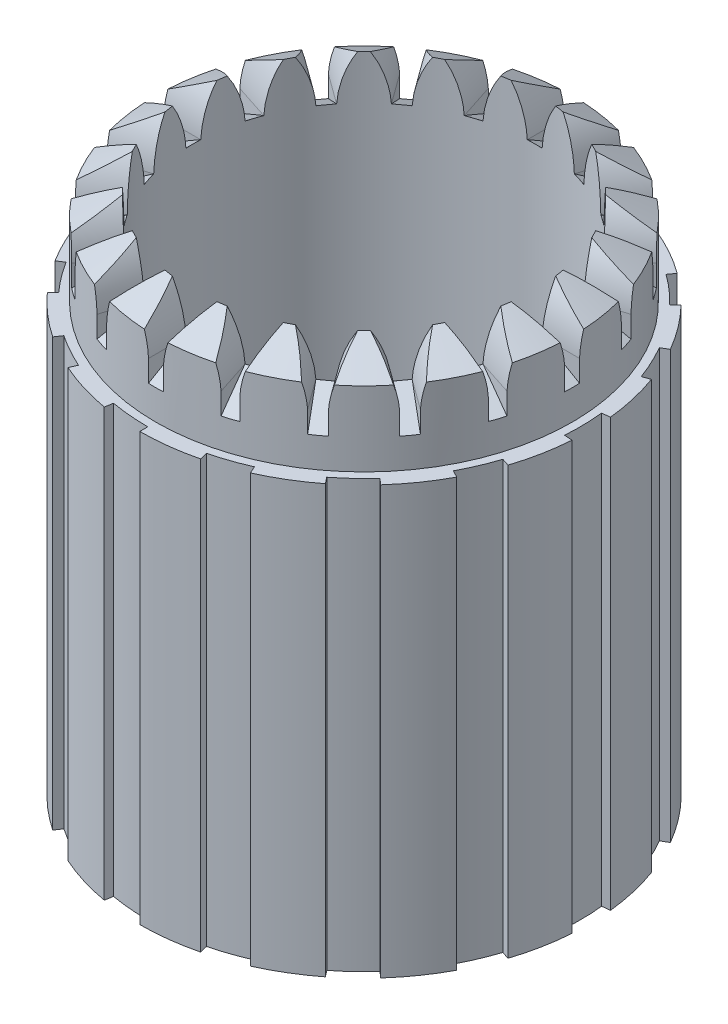
SolidWorks part; units mm, degrees
ref_plane "Front Plane" through (0, 0, 0) normal (0, 0, 1) x (1, 0, 0)
ref_plane "Top Plane" through (0, 0, 0) normal (0, 1, 0) x (1, 0, 0)
ref_plane "Right Plane" through (0, 0, 0) normal (1, 0, 0) x (0, 0, -1)
sketch "Sketch1" plane through (0, 0, 0) normal (0, 1, 0) x (1, 0, 0)
  circle A0 centre (0, 0) radius 21
  dimension "D1" = 42
extrude "Boss-Extrude1" add sketch "Sketch1" along normal blind 40
sketch "Sketch3" plane through (0, 40, 0) normal (0, 1, 0) x (1, 0, 0)
  circle A0 centre (0, 0) radius 19.5
  dimension "D1" = 39
extrude "Boss-Extrude2" add sketch "Sketch3" along normal blind 9
sketch "Sketch4" plane through (0, 49, 0) normal (0, 1, 0) x (1, 0, 0)
  circle A0 centre (0, 0) radius 16
  dimension "D1" = 32
extrude "Cut-Extrude1" cut sketch "Sketch4" against normal blind 59
sketch "Sketch5" plane through (0, 0, 0) normal (0, -1, 0) x (1, 0, 0)
  line L0 (0, 21) -> (0, -21) construction
  line L1 (0, 21) -> (0, 20.25)
  line L2 (5.0804, 20.3762) -> (4.8989, 19.6485)
  line L3 (12.9289, 16.5482) -> (12.4671, 15.9572)
  line L4 (8.5415, 19.1845) -> (8.2364, 18.4993)
  line L5 (18.5419, 9.8589) -> (17.8797, 9.5068)
  line L6 (15.606, 14.0517) -> (15.0487, 13.5499)
  line L7 (20.9488, 1.4649) -> (20.2007, 1.4126)
  line L8 (19.9722, 6.4894) -> (19.2589, 6.2576)
  line L9 (19.7335, -7.1824) -> (19.0288, -6.9259)
  line L10 (20.885, -2.1951) -> (20.1391, -2.1167)
  line L11 (15.1061, -14.5878) -> (14.5666, -14.0668)
  line L12 (18.1865, -10.5) -> (17.537, -10.125)
  line L13 (7.8667, -19.4709) -> (7.5858, -18.7755)
  line L14 (12.3435, -16.9894) -> (11.9027, -16.3826)
  line L15 (-0.7329, -20.9872) -> (-0.7067, -20.2377)
  line L16 (4.3661, -20.5411) -> (4.2102, -19.8075)
  line L17 (-9.2058, -18.8747) -> (-8.877, -18.2006)
  line L18 (-4.3661, -20.5411) -> (-4.2102, -19.8075)
  line L19 (-16.0869, -13.4985) -> (-15.5124, -13.0164)
  line L20 (-12.3435, -16.9894) -> (-11.9027, -16.3826)
  line L21 (-20.1865, -5.7884) -> (-19.4655, -5.5817)
  line L22 (-18.1865, -10.5) -> (-17.537, -10.125)
  line L23 (-20.7956, 2.9226) -> (-20.0529, 2.8183)
  line L24 (-20.885, -2.1951) -> (-20.1391, -2.1167)
  line L25 (-17.809, 11.1283) -> (-17.173, 10.7309)
  line L26 (-19.9722, 6.4894) -> (-19.2589, 6.2576)
  line L27 (-11.7431, 17.4098) -> (-11.3237, 16.788)
  line L28 (-15.606, 14.0517) -> (-15.0487, 13.5499)
  line L29 (-3.6466, 20.681) -> (-3.5164, 19.9424)
  line L30 (-8.5415, 19.1845) -> (-8.2364, 18.4993)
  circle A0 centre (0, 0) radius 20.25 construction
  circle A1 centre (0, 0) radius 21 construction
  arc A2 (-8.5415, 19.1845) -> (-11.7431, 17.4098) centre (0, 0) ccw
  arc A3 (-15.0487, 13.5499) -> (-17.173, 10.7309) centre (0, 0) ccw
  arc A4 (-8.2364, 18.4993) -> (-11.3237, 16.788) centre (0, 0) ccw
  arc A5 (-19.2589, 6.2576) -> (-20.0529, 2.8183) centre (0, 0) ccw
  arc A6 (-20.1391, -2.1167) -> (-19.4655, -5.5817) centre (0, 0) ccw
  arc A7 (-17.537, -10.125) -> (-15.5124, -13.0164) centre (0, 0) ccw
  arc A8 (-11.9027, -16.3826) -> (-8.877, -18.2006) centre (0, 0) ccw
  arc A9 (-4.2102, -19.8075) -> (0, -20.25) centre (0, 0) ccw
  arc A10 (4.2102, -19.8075) -> (7.5858, -18.7755) centre (0, 0) ccw
  arc A11 (11.9027, -16.3826) -> (14.5666, -14.0668) centre (0, 0) ccw
  arc A12 (17.537, -10.125) -> (19.0288, -6.9259) centre (0, 0) ccw
  arc A13 (20.1391, -2.1167) -> (20.2007, 1.4126) centre (0, 0) ccw
  arc A14 (19.2589, 6.2576) -> (17.8797, 9.5068) centre (0, 0) ccw
  arc A15 (15.0487, 13.5499) -> (12.4671, 15.9572) centre (0, 0) ccw
  arc A16 (8.2364, 18.4993) -> (4.8989, 19.6485) centre (0, 0) ccw
  arc A17 (0, 20.25) -> (-3.5164, 19.9424) centre (0, 0) ccw
  arc A18 (0, 21) -> (-3.6466, 20.681) centre (0, 0) ccw
  arc A19 (8.5415, 19.1845) -> (5.0804, 20.3762) centre (0, 0) ccw
  arc A20 (15.606, 14.0517) -> (12.9289, 16.5482) centre (0, 0) ccw
  arc A21 (19.9722, 6.4894) -> (18.5419, 9.8589) centre (0, 0) ccw
  arc A22 (20.885, -2.1951) -> (20.9488, 1.4649) centre (0, 0) ccw
  arc A23 (18.1865, -10.5) -> (19.7335, -7.1824) centre (0, 0) ccw
  arc A24 (12.3435, -16.9894) -> (15.1061, -14.5878) centre (0, 0) ccw
  arc A25 (4.3661, -20.5411) -> (7.8667, -19.4709) centre (0, 0) ccw
  arc A26 (-4.3661, -20.5411) -> (0, -21) centre (0, 0) ccw
  arc A27 (-12.3435, -16.9894) -> (-9.2058, -18.8747) centre (0, 0) ccw
  arc A28 (-18.1865, -10.5) -> (-16.0869, -13.4985) centre (0, 0) ccw
  arc A29 (-20.885, -2.1951) -> (-20.1865, -5.7884) centre (0, 0) ccw
  arc A30 (-19.9722, 6.4894) -> (-20.7956, 2.9226) centre (0, 0) ccw
  arc A31 (-15.606, 14.0517) -> (-17.809, 11.1283) centre (0, 0) ccw
  point P70 (0, 0)
  circle M2 centre (0, 0) radius 21
  dimension "D1" = 40.5
  dimension "D2" = 14
  dimension "D3" = 15
extrude "Cut-Extrude2" cut sketch "Sketch5" against normal blind 50 contours A16 L4 L2 M2 | A17 L1 L29 M2 | A7 L22 L19 M2 | A8 L20 L17 M2 | A9 L18 L15 M2 | A10 L16 L13 M2 | A12 L12 L9 M2 | A11 L14 L11 M2 | A13 L10 L7 M2 | A14 L8 L5 M2 | A15 L6 L3 M2 | A2 L27 A4 L30 | A31 L25 A3 L28 | A30 L23 A5 L26 | A29 L21 A6 L24
sketch "Sketch8" plane through (0, 0, 0) normal (0, 0, 1) x (1, 0, 0)
  line L0 (16, 49) -> (19.5, 49)
  line L1 (19.5, 40) -> (19.5, 49) construction
  line L2 (19.5, 46.9793) -> (16, 49)
  line L3 (16, 49) -> (-16, 49) construction
  line L4 (19.5, 49) -> (19.5, 46.9793)
  dimension "D1" = 30
revolve "Cut-Revolve4" cut sketch "Sketch8" angle 360 about axis through (0, 49, 0) along (0, -1, 0)
sketch "Sketch9" plane through (0, 0, 0) normal (1, 0, 0) x (0, 0, -1)
  line L0 (0, 49) -> (0, 0) construction
  line L1 (-16, 49) -> (16, 49) construction
  line L2 (-0.695, 44.82) -> (0.695, 44.82)
  line L3 (-2.085, 49) -> (2.085, 49)
  arc A0 (-0.695, 44.82) -> (-2.085, 49) centre (-8.9836, 44.3849) ccw
  arc A1 (0.695, 44.82) -> (2.085, 49) centre (8.9836, 44.3849) cw
  dimension "D2" = 8.3
  dimension "D3" = 8.3
  dimension "D1" = 4.18
  dimension "D4" = 1.39
  dimension "D5" = 0.695
  dimension "D6" = 1.39
  dimension "D7" = 1.39
extrude "Cut-Extrude3" cut sketch "Sketch9" along normal blind 24
pattern_circular "CirPattern2" count 20 over 360 about axis through (0, -10, 0) along (0, 1, 0) of "Cut-Extrude3"
sketch "Sketch10" plane through (0, 0, 0) normal (1, 0, 0) x (0, 0, -1)
  line L0 (-16, 44.82) -> (-19.5, 44.82)
  line L1 (-16, 44.82) -> (-19.5, 42.7993)
  line L2 (-19.5, 44.82) -> (-19.5, 40) construction
  line L3 (-19.5, 42.7993) -> (-19.5, 44.82)
  dimension "D1" = 30
extrude "Cut-Extrude4" cut sketch "Sketch10" against normal mid plane 1.39
pattern_circular "CirPattern3" count 20 over 360 about axis through (0, 0, 0) along (0, 1, 0) of "Cut-Extrude4"
